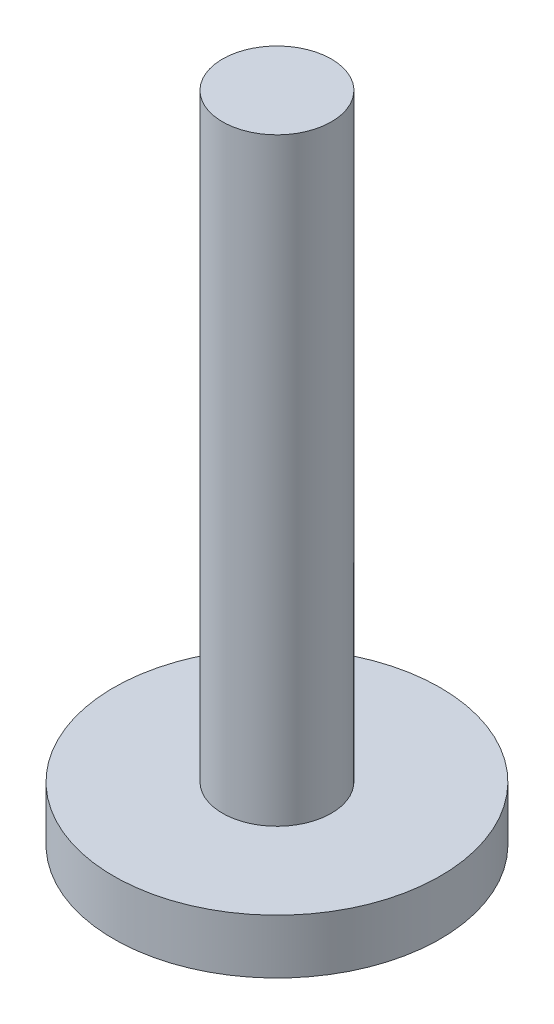
SolidWorks part; units mm, degrees
ref_plane "Front Plane" through (0, 0, 0) normal (0, 0, 1) x (1, 0, 0)
ref_plane "Top Plane" through (0, 0, 0) normal (0, 1, 0) x (1, 0, 0)
ref_plane "Right Plane" through (0, 0, 0) normal (1, 0, 0) x (0, 0, -1)
sketch "Sketch1" plane through (0, 0, 0) normal (0, 0, 1) x (1, 0, 0)
  line L0 (0, 0) -> (0, 76.2)
  line L1 (0, 76.2) -> (6.35, 76.2)
  line L2 (6.35, 76.2) -> (6.35, 6.35)
  line L3 (6.35, 6.35) -> (19.05, 6.35)
  line L4 (19.05, 6.35) -> (19.05, 0)
  line L5 (19.05, 0) -> (0, 0)
  dimension "D1" = 76.2
  dimension "D2" = 6.35
  dimension "D3" = 19.05
  dimension "D4" = 6.35
revolve "Revolve1" add sketch "Sketch1" angle 360 about L0
